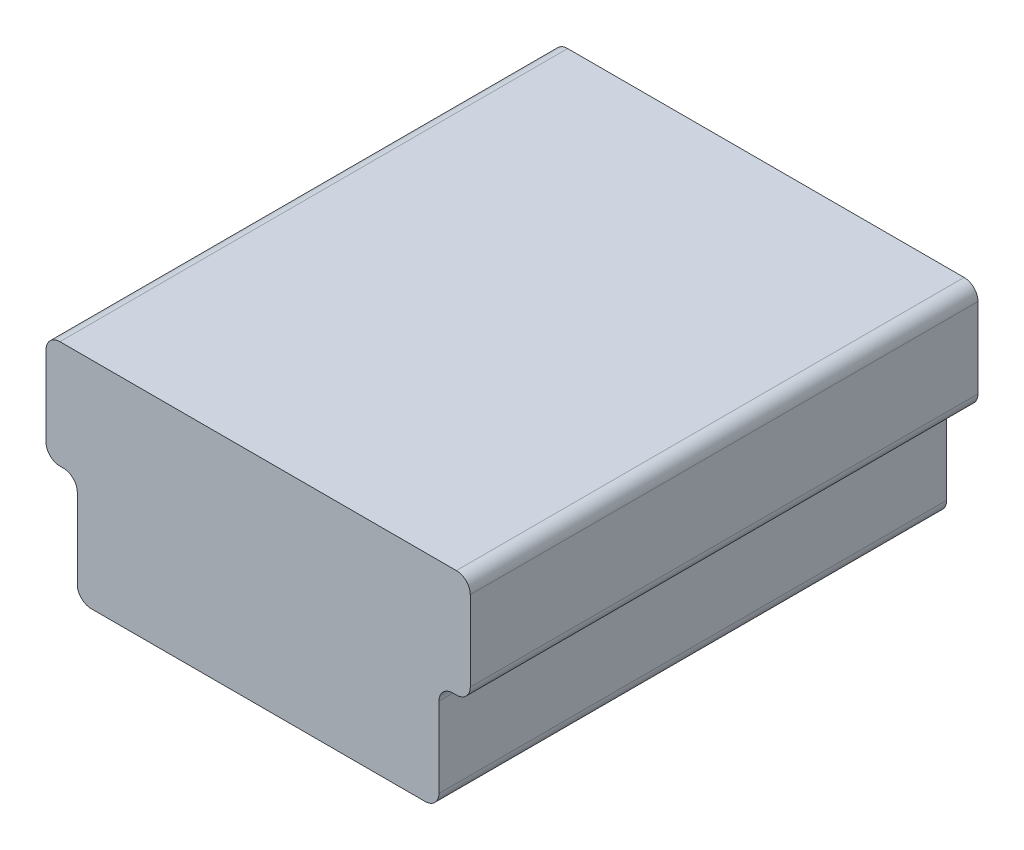
SolidWorks part; units mm, degrees
ref_plane "Front Plane" through (0, 0, 0) normal (0, 0, 1) x (1, 0, 0)
ref_plane "Top Plane" through (0, 0, 0) normal (0, 1, 0) x (1, 0, 0)
ref_plane "Right Plane" through (0, 0, 0) normal (1, 0, 0) x (0, 0, -1)
ref_plane "Plane1" through (0, 0, 0) normal (0, -1, 0) x (1, 0, 0)
sketch "Sketch1" plane through (0, 0, 0) normal (0, -1, 0) x (1, 0, 0)
  line L0 (-3.8735, 0) -> (3.8735, 0)
  line L1 (3.8735, 0) -> (3.8735, 9.271)
  line L2 (3.8735, 9.271) -> (-3.8735, 9.271)
  line L3 (-3.8735, 9.271) -> (-3.8735, 0)
extrude "Boss-Extrude1" add sketch "Sketch1" against normal blind 3.937
sketch "Sketch2" plane through (0, 0, 0) normal (0, 0, -1) x (-1, 0, 0)
  line L0 (-3.302, 0) -> (-3.302, 1.9685)
  line L1 (-3.302, 1.9685) -> (-3.8735, 1.9685)
  line L2 (-3.8735, 1.9685) -> (-3.8735, 0)
  line L3 (-3.8735, 0) -> (-3.302, 0)
extrude "Cut-Extrude1" cut sketch "Sketch2" against normal through all
sketch "Sketch3" plane through (0, 0, 0) normal (0, 0, -1) x (-1, 0, 0)
  line L0 (3.8735, 1.9685) -> (3.302, 1.9685)
  line L1 (3.302, 1.9685) -> (3.302, 0)
  line L2 (3.302, 0) -> (3.8735, 0)
  line L3 (3.8735, 0) -> (3.8735, 1.9685)
extrude "Cut-Extrude2" cut sketch "Sketch3" against normal through all
sketch "Sketch4" plane through (0, 0, 0) normal (0, 0, -1) x (-1, 0, 0)
  line L0 (3.4925, 2.3463) -> (3.4925, 3.556)
  line L1 (3.4925, 3.556) -> (-3.4925, 3.556)
  line L2 (-3.4925, 3.556) -> (-3.4925, 2.3463)
  line L3 (-2.921, 1.7145) -> (-2.921, 0.381)
  line L4 (-2.921, 0.381) -> (2.921, 0.381)
  line L5 (2.921, 0.381) -> (2.921, 1.7145)
  arc A0 (2.921, 1.7145) -> (3.4925, 2.3463) centre (3.556, 1.7145) cw
  arc A1 (-3.4925, 2.3463) -> (-2.921, 1.7145) centre (-3.556, 1.7145) cw
extrude "Cut-Extrude3" cut sketch "Sketch4" against normal blind 8.89
sketch "Sketch5" plane through (0, 0, 8.89) normal (0, 0, -1) x (-1, 0, 0)
  line L0 (-2.2225, 1.016) -> (-2.2225, 2.54)
  line L1 (-2.2225, 2.54) -> (2.2225, 2.54)
  line L2 (2.2225, 2.54) -> (2.2225, 1.016)
  line L3 (2.2225, 1.016) -> (-2.2225, 1.016)
extrude "Boss-Extrude2" add sketch "Sketch5" along normal blind 8.001
chamfer "Chamfer1" distance 0.508 angle 45 2 edges at (2.2225, 1.016, 4.8895) (-2.2225, 1.016, 4.8895)
fillet "Fillet1" radius 0.254 8 edges at (3.8735, 3.937, 4.6355) (3.8735, 1.9685, 4.6355) (-3.302, 0, 4.6355) (3.302, 1.9685, 4.6355) (-3.8735, 3.937, 4.6355) (-3.302, 1.9685, 4.6355) (3.302, 0, 4.6355) (-3.8735, 1.9685, 4.6355)
